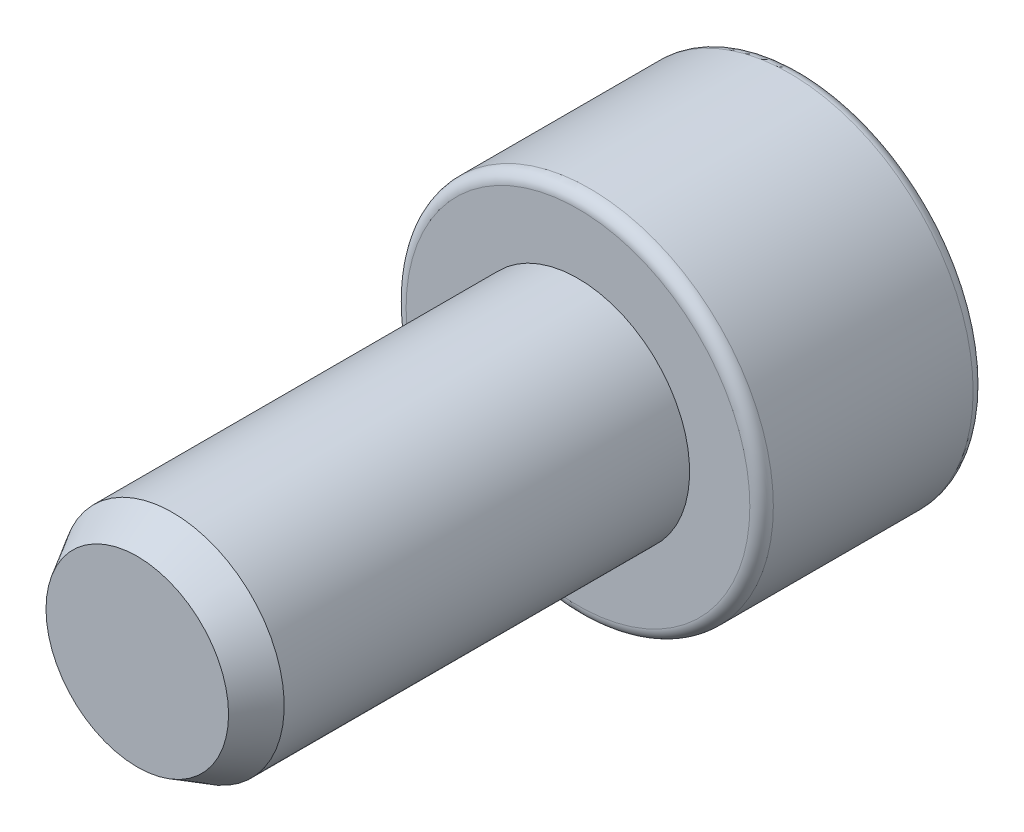
SolidWorks part; units mm, degrees
ref_plane "Front Plane" through (0, 0, 0) normal (0, 0, 1) x (1, 0, 0)
ref_plane "Top Plane" through (0, 0, 0) normal (0, 1, 0) x (1, 0, 0)
ref_plane "Right Plane" through (0, 0, 0) normal (1, 0, 0) x (0, 0, -1)
sketch "Sketch1" plane through (0, 0, 0) normal (0, 1, 0) x (1, 0, 0)
  line L0 (0, 0) -> (3.7147, 0)
  line L1 (3.9687, -0.254) -> (3.9687, -4.572)
  line L2 (3.7147, -4.826) -> (0, -4.826)
  line L3 (0, 0) -> (0, 1.0712) construction
  line L4 (0, 0) -> (0, -4.826)
  line L5 (0, 0) -> (0.1848, 0.1731) construction
  arc A0 (3.9687, -4.572) -> (3.7147, -4.826) centre (3.7147, -4.572) cw
  arc A1 (3.9687, -0.254) -> (3.7147, 0) centre (3.7147, -0.254) ccw
  point P6 (3.9687, -4.826)
  point P9 (3.9687, 0)
revolve "Revolve1" add sketch "Sketch1" angle 360 about L3
sketch "Sketch2" plane through (0, 0, 0) normal (0, 0, -1) x (-1, 0, 0)
  line L1 (0, 2.2914) -> (-1.9844, 1.1457)
  line L2 (-1.9844, 1.1457) -> (-1.9844, -1.1457)
  line L3 (-1.9844, -1.1457) -> (0, -2.2914)
  line L4 (0, -2.2914) -> (1.9844, -1.1457)
  line L5 (1.9844, -1.1457) -> (1.9844, 1.1457)
  line L6 (1.9844, 1.1457) -> (0, 2.2914)
  circle A0 centre (0, 0) radius 1.9844 construction
extrude "Cut-Extrude1" cut sketch "Sketch2" against normal blind 2.54
sketch "Sketch3" plane through (0, 0, 4.826) normal (0, 0, 1) x (1, 0, 0)
  circle A0 centre (0, 0) radius 2.413
  dimension "D1" = 4.826
extrude "Boss-Extrude1" add sketch "Sketch3" along normal blind 9.525
chamfer "Chamfer1" distance 0.762 angle 30 1 edges at (2.413, 0, 14.351)
